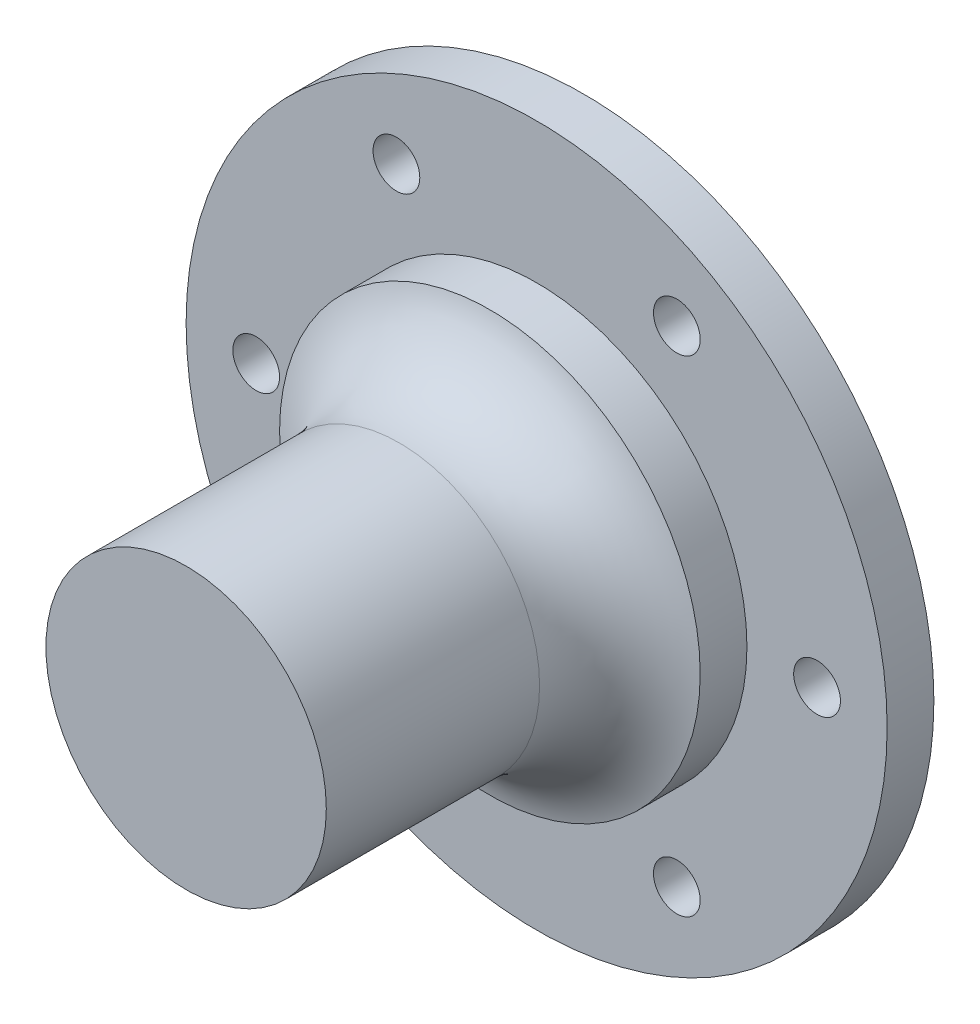
SolidWorks part; units mm, degrees
ref_plane "Front Plane" through (0, 0, 0) normal (0, 0, 1) x (1, 0, 0)
ref_plane "Top Plane" through (0, 0, 0) normal (0, 1, 0) x (1, 0, 0)
ref_plane "Right Plane" through (0, 0, 0) normal (1, 0, 0) x (0, 0, -1)
sketch "Sketch1" plane through (0, 0, 0) normal (0, 0, 1) x (1, 0, 0)
  circle A0 centre (0, 0) radius 75
  dimension "D1" = 150
extrude "Boss-Extrude1" add sketch "Sketch1" along normal blind 10
sketch "Sketch2" plane through (0, 0, 0) normal (1, 0, 0) x (0, 0, -1)
  line L0 (-1000, 0) -> (49000, 0) construction
  line L1 (-10, 45) -> (-20, 45)
  line L2 (-10, 75) -> (-10, -75) construction
  line L3 (-39.3649, 30) -> (-85, 30)
  line L4 (-85, 30) -> (-85, 0)
  line L5 (-10, 45) -> (-10, 0)
  line L6 (-10, 0) -> (-85, 0)
  arc A0 (-20, 45) -> (-39.3649, 30) centre (-39.3649, 50) cw
  point P11 (-15, 45)
  dimension "D1" = 45
  dimension "D3" = 20
  dimension "D2" = 10
  dimension "D4" = 30
  dimension "D5" = 75
revolve "Revolve1" add sketch "Sketch2" angle 360 about L0
sketch "Sketch3" plane through (0, 0, 0) normal (0, 0, -1) x (-1, 0, 0)
  circle A0 centre (0, 0) radius 40
  dimension "D1" = 80
extrude "Boss-Extrude2" add sketch "Sketch3" along normal blind 10
sketch "Sketch4" plane through (0, 0, -10) normal (0, 0, -1) x (-1, 0, 0)
  circle A0 centre (0, 0) radius 35
  dimension "D1" = 70
extrude "Cut-Extrude1" cut sketch "Sketch4" against normal blind 20
sketch "Sketch5" plane through (0, 0, 10) normal (0, 0, 1) x (1, 0, 0)
  circle A0 centre (0, 0) radius 60 construction
  circle A1 centre (60, 0) radius 5
  circle A2 centre (30, -51.9615) radius 5
  circle A3 centre (-30, -51.9615) radius 5
  circle A4 centre (-60, 0) radius 5
  circle A5 centre (-30, 51.9615) radius 5
  circle A6 centre (30, 51.9615) radius 5
  point P17 (0, 0)
  dimension "D1" = 120
  dimension "D2" = 10
  dimension "D3" = 6
extrude "Cut-Extrude2" cut sketch "Sketch5" against normal blind 20
